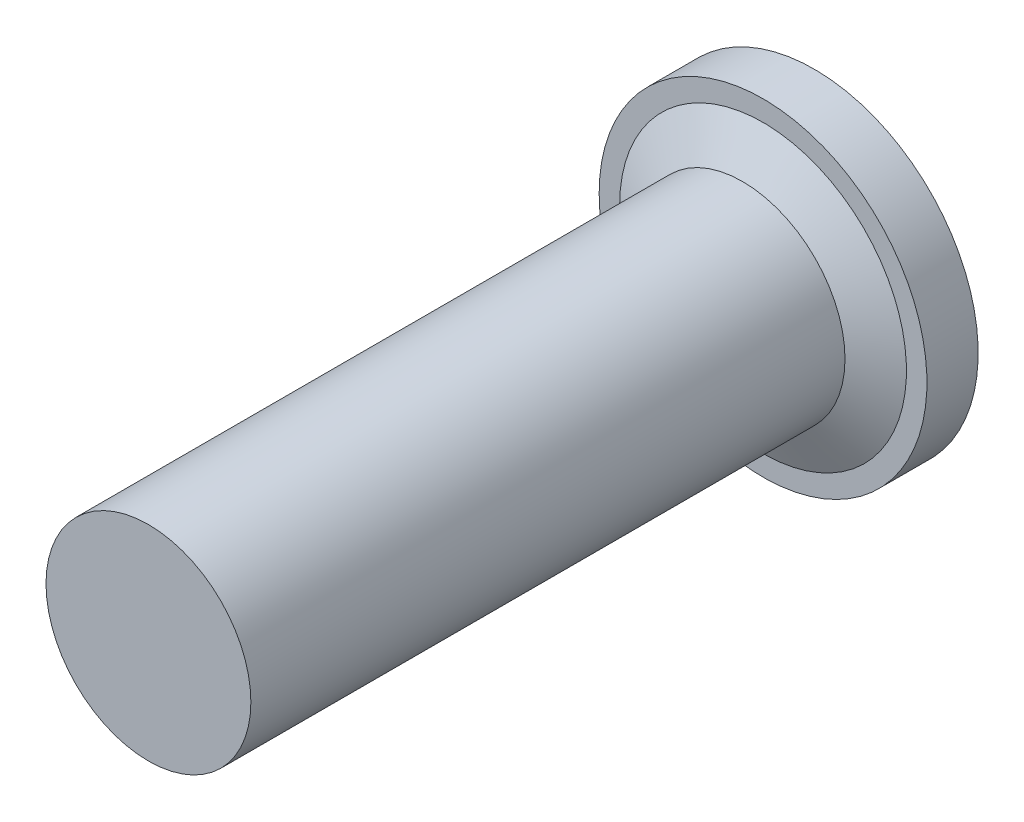
SolidWorks part; units mm, degrees
ref_plane "Front Plane" through (0, 0, 0) normal (0, 0, 1) x (1, 0, 0)
ref_plane "Top Plane" through (0, 0, 0) normal (0, 1, 0) x (1, 0, 0)
ref_plane "Right Plane" through (0, 0, 0) normal (1, 0, 0) x (0, 0, -1)
sketch "Sketch1" plane through (0, 0, 0) normal (0, 1, 0) x (1, 0, 0)
  line L0 (0, 338.8166) -> (0, -341.1901) construction
  line L1 (0, 300.9065) -> (203.2, 300.9065)
  line L2 (203.2, 300.9065) -> (203.2, 237.4065)
  line L3 (203.2, 237.4065) -> (177.8, 237.4065)
  line L4 (177.8, 237.4065) -> (127, 212.0065)
  line L5 (127, 212.0065) -> (127, -524.5935)
  line L6 (127, -524.5935) -> (0, -524.5935)
  line L7 (0, 300.9065) -> (0, -524.5935)
  dimension "D1" = 203.2
  dimension "D2" = 177.8
  dimension "D3" = 127
  dimension "D4" = 63.5
  dimension "D5" = 25.4
  dimension "D6" = 736.6
revolve "Revolve2" add sketch "Sketch1" angle 360 about L0
